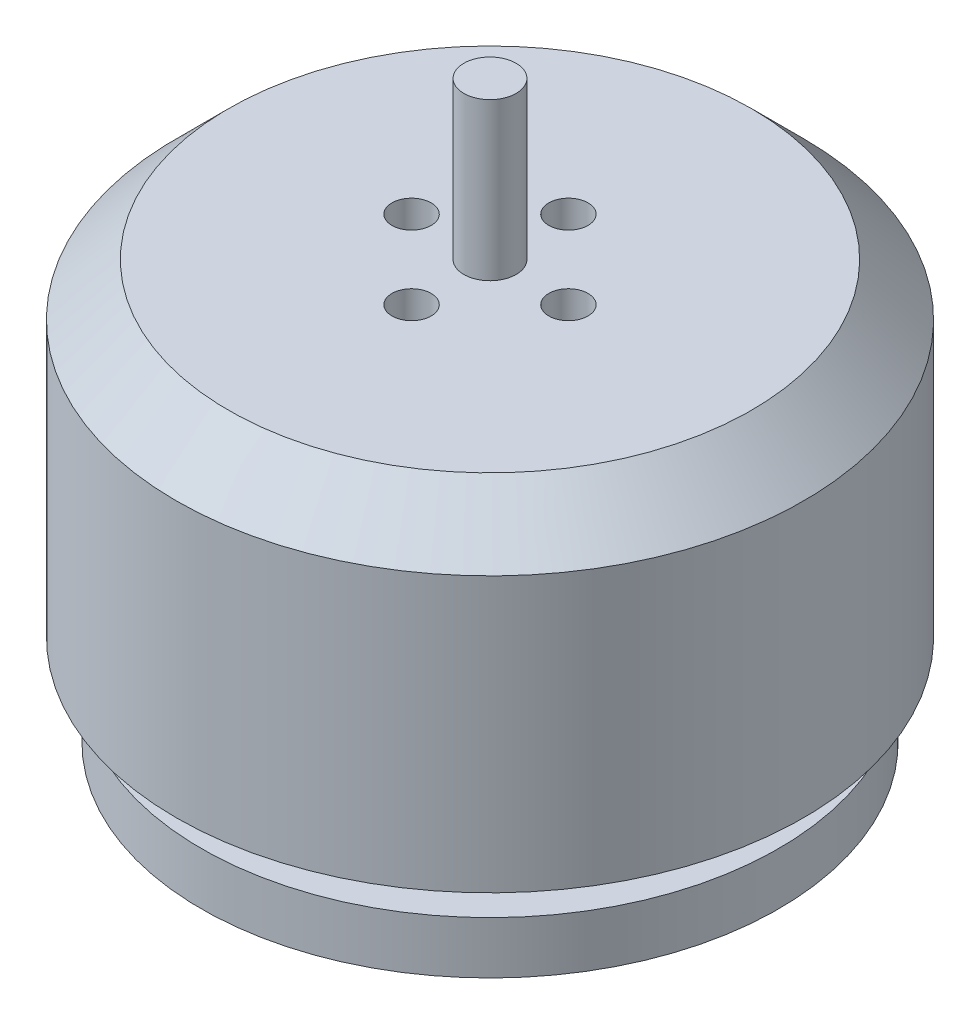
SolidWorks part; units mm, degrees
ref_plane "Front Plane" through (0, 0, 0) normal (0, 0, 1) x (1, 0, 0)
ref_plane "Top Plane" through (0, 0, 0) normal (0, 1, 0) x (1, 0, 0)
ref_plane "Right Plane" through (0, 0, 0) normal (1, 0, 0) x (0, 0, -1)
sketch "Sketch1" plane through (0, 0, 0) normal (0, 0, 1) x (1, 0, 0)
  line L0 (0, 0) -> (22.08, 0)
  line L1 (22.08, 0) -> (22.08, 4)
  line L2 (22.08, 4) -> (16.8, 4)
  line L3 (16.8, 4) -> (16.8, 7)
  line L4 (16.8, 7) -> (24, 7)
  line L5 (24, 7) -> (24, 28)
  line L6 (24, 28) -> (20, 32)
  line L7 (20, 32) -> (2, 32)
  line L8 (2, 32) -> (2, 44)
  line L9 (2, 44) -> (0, 44)
  line L10 (0, 44) -> (0, 0)
  line L11 (0, -10) -> (0, 1000) construction
revolve "Revolve1" add sketch "Sketch1" angle 360 about L11
sketch "Sketch2" plane through (0, 0, 0) normal (0, 1, 0) x (1, 0, 0)
  circle A0 centre (8.84, -8.84) radius 1.5
  circle A1 centre (8.84, 8.84) radius 1.5
  circle A2 centre (-8.84, -8.84) radius 1.5
  circle A3 centre (-8.84, 8.84) radius 1.5
extrude "Cut-Extrude1" cut sketch "Sketch2" along normal blind 3.3
ref_plane "Plane1" through (0, 32, 0) normal (0, 1, 0) x (1, 0, 0)
sketch "Sketch3" plane through (0, 32, 0) normal (0, 1, 0) x (1, 0, 0)
  circle A0 centre (6, 0) radius 1.5
  circle A1 centre (-6, 0) radius 1.5
  circle A2 centre (0, -6) radius 1.5
  circle A3 centre (0, 6) radius 1.5
extrude "Cut-Extrude2" cut sketch "Sketch3" against normal blind 8
